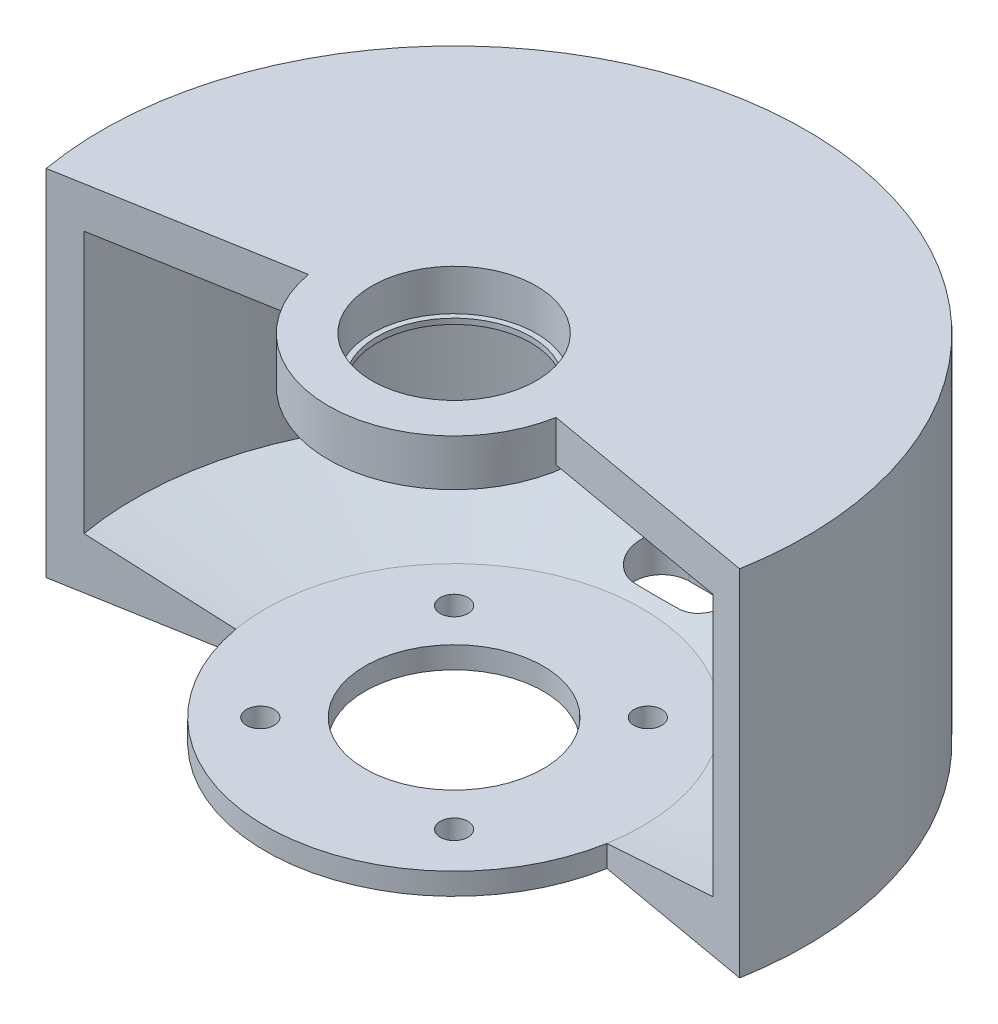
SolidWorks part; units mm, degrees
ref_plane "Front Plane" through (0, 0, 0) normal (0, 0, 1) x (1, 0, 0)
ref_plane "Top Plane" through (0, 0, 0) normal (0, 1, 0) x (1, 0, 0)
ref_plane "Right Plane" through (0, 0, 0) normal (1, 0, 0) x (0, 0, -1)
sketch "Sketch2" plane through (0, 0, 0) normal (0, 1, 0) x (1, 0, 0)
  circle A1 centre (-14.1421, 14.1421) radius 1.65 construction
  circle A2 centre (14.1421, 14.1421) radius 1.65 construction
  circle A3 centre (14.1421, -14.1421) radius 1.65 construction
  circle A4 centre (-14.1421, -14.1421) radius 1.65 construction
  circle A5 centre (0, 0) radius 13
  circle A6 centre (-14.1421, 14.1421) radius 1.65 construction
  circle A7 centre (14.1421, 14.1421) radius 1.65 construction
  circle A8 centre (14.1421, -14.1421) radius 1.65 construction
  circle A9 centre (-14.1421, -14.1421) radius 1.65 construction
  arc A10 (10.7886, -7.253) -> (10.7886, 7.253) centre (0, 0) ccw construction
  circle A11 centre (0, 0) radius 27.5
  circle A12 centre (0, 0) radius 27.5 construction
  circle A13 centre (-14.1421, -14.1421) radius 2.025
  circle A14 centre (14.1421, -14.1421) radius 2.025
  circle A15 centre (14.1421, 14.1421) radius 2.025
  circle A16 centre (-14.1421, 14.1421) radius 2.025
  dimension "D1" = 4.05
extrude "Boss-Extrude1" add sketch "Sketch2" against normal blind 3.175 from surface at -14.125
sketch "Sketch3" plane through (0, 0, 0) normal (0, 1, 0) x (1, 0, 0)
  circle A0 centre (0, 0) radius 12
  circle A1 centre (0, 0) radius 12 construction
  circle A2 centre (0, 0) radius 18.35
  dimension "D1" = 6.35
extrude "Boss-Extrude2" add sketch "Sketch3" along normal blind 6 from surface separate body
sketch "Sketch4" plane through (0, 0, 0) normal (1, 0, 0) x (0, 0, -1)
  line L0 (27.5, -17.3) -> (51.3863, -17.3)
  line L1 (51.3863, -17.3) -> (51.3863, 34.4275)
  line L2 (27.5, -14.125) -> (46.6238, -9.7953)
  line L3 (36.33, -12.1258) -> (45.83, -9.975) construction
  line L4 (45.83, -9.975) -> (45.83, 5.525) construction
  line L5 (46.6238, -9.7953) -> (46.6238, 28.4275)
  line L7 (46.6238, 28.4275) -> (18.35, 28.4275)
  line L9 (51.3863, 34.4275) -> (18.35, 34.4275)
  line L10 (18.35, 34.4275) -> (18.35, 28.4275)
  line L16 (0, -14.125) -> (0, 28.4275) construction
  line L17 (13, -14.125) -> (-13, -14.125) construction
  line L18 (-18.35, 28.4275) -> (18.35, 28.4275) construction
  line L19 (27.5, -17.3) -> (27.5, -14.125)
  dimension "D1" = 0.7937
  dimension "D2" = 4.7625
revolve "Revolve1" add sketch "Sketch4" angle 200 mid plane about L16
sketch "Sketch5" plane through (0, 28.4275, 0) normal (0, -1, 0) x (1, 0, 0)
  circle A0 centre (0, 0) radius 11.2063
  circle A1 centre (0, 0) radius 18.35
  arc A2 (18.0712, 3.1864) -> (-18.0712, 3.1864) centre (0, 0) ccw construction
  circle A3 centre (0, 0) radius 12 construction
  dimension "D1" = 0.7937
extrude "Boss-Extrude3" add sketch "Sketch5" along normal blind 0.7937
fillet "Fillet1" [suppressed] radius 1.5875
sketch "Sketch6" plane through (0, -17.3, 0) normal (0, -1, 0) x (-1, 0, 0)
  line L0 (3.25, 33.58) -> (-3.25, 33.58) construction
  line L1 (3.25, 29.6113) -> (-3.25, 29.6113)
  line L2 (3.25, 37.5488) -> (-3.25, 37.5488)
  arc A0 (3.25, 29.6113) -> (3.25, 37.5488) centre (3.25, 33.58) ccw
  arc A1 (-3.25, 37.5488) -> (-3.25, 29.6113) centre (-3.25, 33.58) ccw
  point P4 (0, 33.58)
  dimension "D1" = 7.9375
extrude "Cut-Extrude1" cut sketch "Sketch6" against normal up to next
